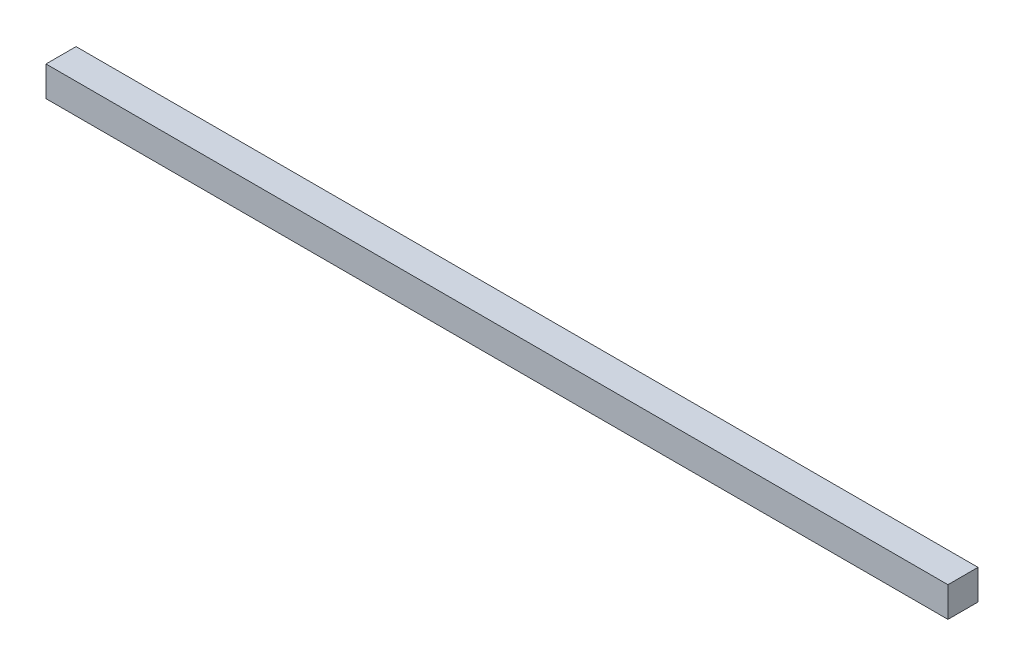
SolidWorks part; units mm, degrees
ref_plane "Front Plane" through (0, 0, 0) normal (0, 0, 1) x (1, 0, 0)
ref_plane "Top Plane" through (0, 0, 0) normal (0, 1, 0) x (1, 0, 0)
ref_plane "Right Plane" through (0, 0, 0) normal (1, 0, 0) x (0, 0, -1)
sketch "Sketch1" plane through (0, 0, 0) normal (0, 0, 1) x (1, 0, 0)
  line L0 (-202.0052, 0) -> (178.9948, 0)
  line L1 (178.9948, 0) -> (178.9948, 12.7)
  line L2 (178.9948, 12.7) -> (-202.0052, 12.7)
  line L3 (-202.0052, 12.7) -> (-202.0052, 0)
  dimension "D1" = 381
  dimension "D2" = 12.7
extrude "Boss-Extrude1" add sketch "Sketch1" along normal blind 12.7
